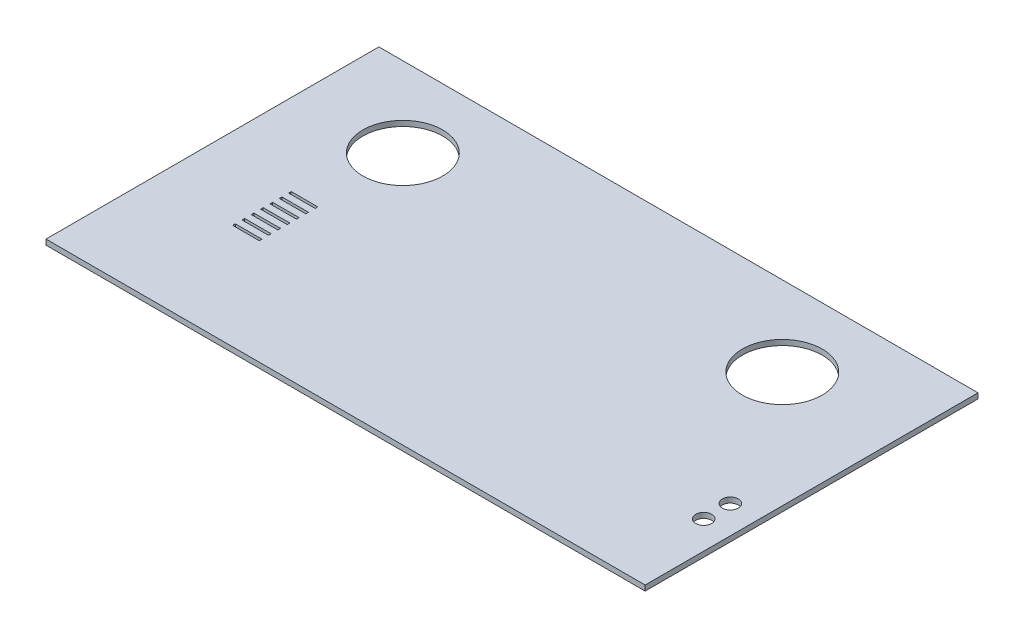
SolidWorks part; units mm, degrees
ref_plane "前基準面" through (0, 0, 0) normal (0, 0, 1) x (1, 0, 0)
ref_plane "上基準面" through (0, 0, 0) normal (0, 1, 0) x (1, 0, 0)
ref_plane "右基準面" through (0, 0, 0) normal (1, 0, 0) x (0, 0, -1)
sketch "草圖1" plane through (0, 0, 0) normal (0, 1, 0) x (1, 0, 0)
  line L0 (0, 0) -> (450, 0)
  line L1 (450, 0) -> (450, 250)
  line L2 (450, 250) -> (0, 250)
  line L3 (0, 250) -> (0, 0)
  dimension "D1" = 450
  dimension "D2" = 250
extrude "填料-伸長1" add sketch "草圖1" along normal blind 4
sketch "草圖2" plane through (0, 4, 0) normal (0, 1, 0) x (1, 0, 0)
  line L0 (0, 250) -> (0, 0) construction
  line L1 (450, 250) -> (0, 250) construction
  circle A0 centre (78, 190) radius 30
  circle A1 centre (363, 190) radius 30
  dimension "D1" = 60
  dimension "D2" = 78
  dimension "D3" = 285
  dimension "D4" = 60
extrude "除料-伸長1" cut sketch "草圖2" against normal through all
sketch "草圖3" plane through (0, 4, 0) normal (0, 1, 0) x (1, 0, 0)
  line L0 (450, 250) -> (0, 250) construction
  line L1 (450, 0) -> (450, 250) construction
  line L2 (0, 250) -> (0, 0) construction
  line L3 (61.17, 123) -> (61.17, 121)
  line L4 (61.17, 121) -> (81.17, 121)
  line L5 (81.17, 121) -> (81.17, 123)
  line L6 (81.17, 123) -> (61.17, 123)
  line L7 (71.17, 123) -> (71.17, 142.4939) construction
  line L8 (61.17, 102) -> (61.17, 100)
  line L9 (61.17, 100) -> (81.17, 100)
  line L10 (81.17, 100) -> (81.17, 102)
  line L11 (81.17, 102) -> (61.17, 102)
  line L12 (61.17, 116) -> (61.17, 114)
  line L13 (61.17, 114) -> (81.17, 114)
  line L14 (81.17, 114) -> (81.17, 116)
  line L15 (81.17, 116) -> (61.17, 116)
  line L16 (61.17, 107) -> (61.17, 109)
  line L17 (61.17, 109) -> (81.17, 109)
  line L18 (81.17, 109) -> (81.17, 107)
  line L19 (81.17, 107) -> (61.17, 107)
  line L20 (61.17, 95) -> (61.17, 93)
  line L21 (61.17, 93) -> (81.17, 93)
  line L22 (81.17, 93) -> (81.17, 95)
  line L23 (81.17, 95) -> (61.17, 95)
  line L24 (61.17, 88) -> (61.17, 86)
  line L25 (61.17, 86) -> (81.17, 86)
  line L26 (81.17, 86) -> (81.17, 88)
  line L27 (81.17, 88) -> (61.17, 88)
  line L28 (61.17, 81) -> (61.17, 79)
  line L29 (61.17, 79) -> (81.17, 79)
  line L30 (81.17, 79) -> (81.17, 81)
  line L31 (81.17, 81) -> (61.17, 81)
  circle A0 centre (71.17, 111) radius 6
  circle A1 centre (71.17, 91) radius 6
  circle A2 centre (429, 85) radius 6
  circle A3 centre (429, 65) radius 6
  dimension "D1" = 12
  dimension "D5" = 139
  dimension "D2" = 165
  dimension "D3" = 21
  dimension "D4" = 20
  dimension "D6" = 71.17
  dimension "D7" = 20
  dimension "D8" = 2
  dimension "D9" = 20
  dimension "D10" = 10
  dimension "D11" = 5
  dimension "D12" = 5
  dimension "D13" = 5
  dimension "D14" = 2
  dimension "D15" = 5
  dimension "D16" = 5
  dimension "D17" = 5
  dimension "D18" = 2
  dimension "D19" = 2
  dimension "D20" = 2
  dimension "D21" = 2
extrude "除料-伸長2" cut sketch "草圖3" against normal through all contours L13 A0 L15 | A0 L15 L12 L13 | L19 A0 L17 | A0 L19 L18 L17 | A0 L17 L16 L19 | A0 L11 L8 L9 L10 | L22 L23 L20 L21 | A1 L27 L24 L25 | L25 A1 L27 | A1 L25 L26 L27 | L30 L31 L28 L29 | L4 L5 L6 L3 | A2 | A3
